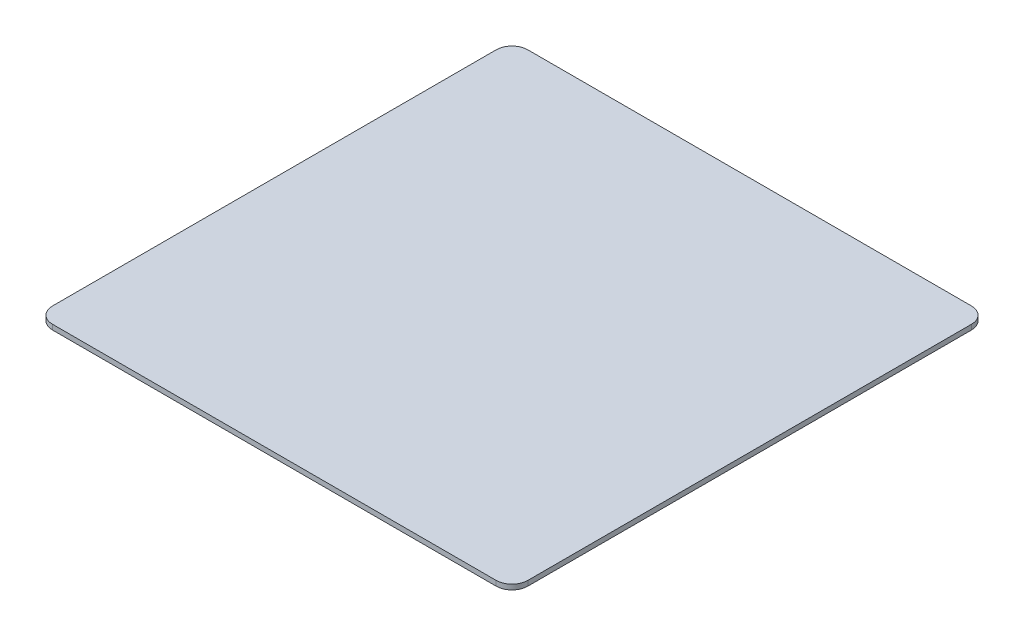
SolidWorks part; units mm, degrees
material "Glass"
ref_plane "Front Plane" through (0, 0, 0) normal (0, 0, 1) x (1, 0, 0)
ref_plane "Top Plane" through (0, 0, 0) normal (0, 1, 0) x (1, 0, 0)
ref_plane "Right Plane" through (0, 0, 0) normal (1, 0, 0) x (0, 0, -1)
sketch "Sketch1" plane through (0, 0, 0) normal (0, 1, 0) x (1, 0, 0)
  line L1 (150, -150) -> (-150, -150)
  line L2 (150, -150) -> (150, 150)
  line L3 (150, 150) -> (-150, 150)
  line L4 (-150, -150) -> (-150, 150)
  line L5 (150, -150) -> (-150, 150) construction
  line L6 (150, 150) -> (-150, -150) construction
  point P0 (0, 0)
  dimension "D1" = 300
extrude "Boss-Extrude1" add sketch "Sketch1" along normal mid plane 3.175
fillet "Fillet1" radius 10 4 edges at (-150, 0, -150) (-150, 0, 150) (150, 0, 150) (150, 0, -150)
